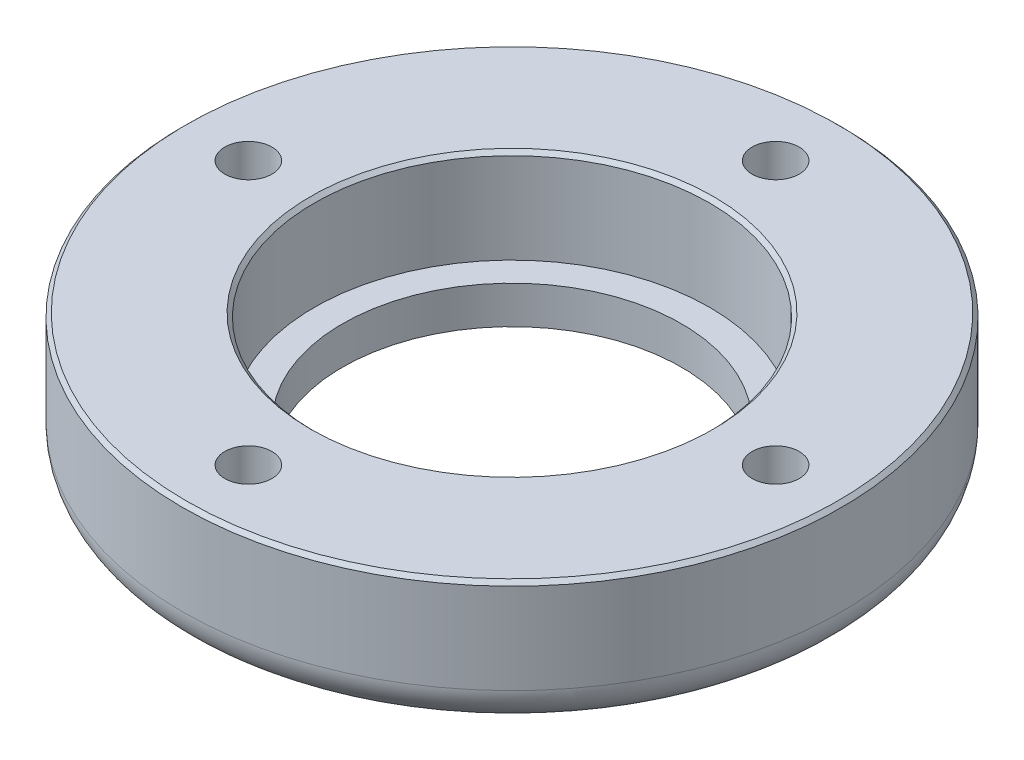
SolidWorks part; units mm, degrees
material "Alliage 1060"
ref_plane "Face" through (0, 0, 0) normal (0, 0, 1) x (1, 0, 0)
ref_plane "Dessus" through (0, 0, 0) normal (0, 1, 0) x (1, 0, 0)
ref_plane "Droite" through (0, 0, 0) normal (1, 0, 0) x (0, 0, -1)
sketch "Esquisse1" plane through (0, 0, 0) normal (1, 0, 0) x (0, 0, -1)
  line L0 (0, 0) -> (0, -70.5308) construction
  line L1 (-9, -2) -> (-9, 0)
  line L2 (-9, 0) -> (-10.5, 0)
  line L3 (-10.5, 0) -> (-10.5, 5)
  line L4 (-10.5, 5) -> (-17.5, 5)
  line L5 (-17.5, 5) -> (-17.5, -2)
  line L6 (-17.5, -2) -> (-9, -2)
  dimension "D1" = 21
  dimension "D2" = 2
  dimension "D3" = 35
  dimension "D4" = 5
  dimension "D5" = 18
revolve "Révolution1" add sketch "Esquisse1" angle 360 about L0
hole_wizard "Trou taraudé M31" positions "Esquisse4" profile "Esquisse3" tap size "M3" standard "Iso" end condition through all
sketch "Esquisse4" plane through (0, 5, 0) normal (0, 1, 0) x (-1, 0, 0)
  circle A0 centre (0, 0) radius 14 construction
  point P0 (0, -14)
  dimension "D1" = 28
cosmetic thread "Filetage de perçage1"
sketch "Esquisse3" plane through (0, 5, -14) normal (1, 0, 0) x (0, 0, 1)
  line L0 (0, 0) -> (0, 7)
  line L1 (0, 7) -> (1.25, 7)
  line L2 (1.25, 7) -> (1.25, 0)
  line L5 (1.25, 0) -> (0, 0)
  line L11 (0, -6.35) -> (0, 107.95) construction
  dimension "Diamètre du trou pour taraudage jusqu'au prochain" = 2.5
  dimension "Profondeur du trou pour taraudage jusqu'au prochain" = 7
pattern_circular "Répétition circulaire1" count 4 over 360 about axis through (0, 0, 0) along (0, 1, 0) of "Trou taraudé M31"
chamfer "Chanfrein1" distance 0.2 angle 45 2 edges at (0, 5, 10.5) (0, 5, 17.5)
fillet "Congé1" radius 2 1 edges at (0, -2, 17.5)
